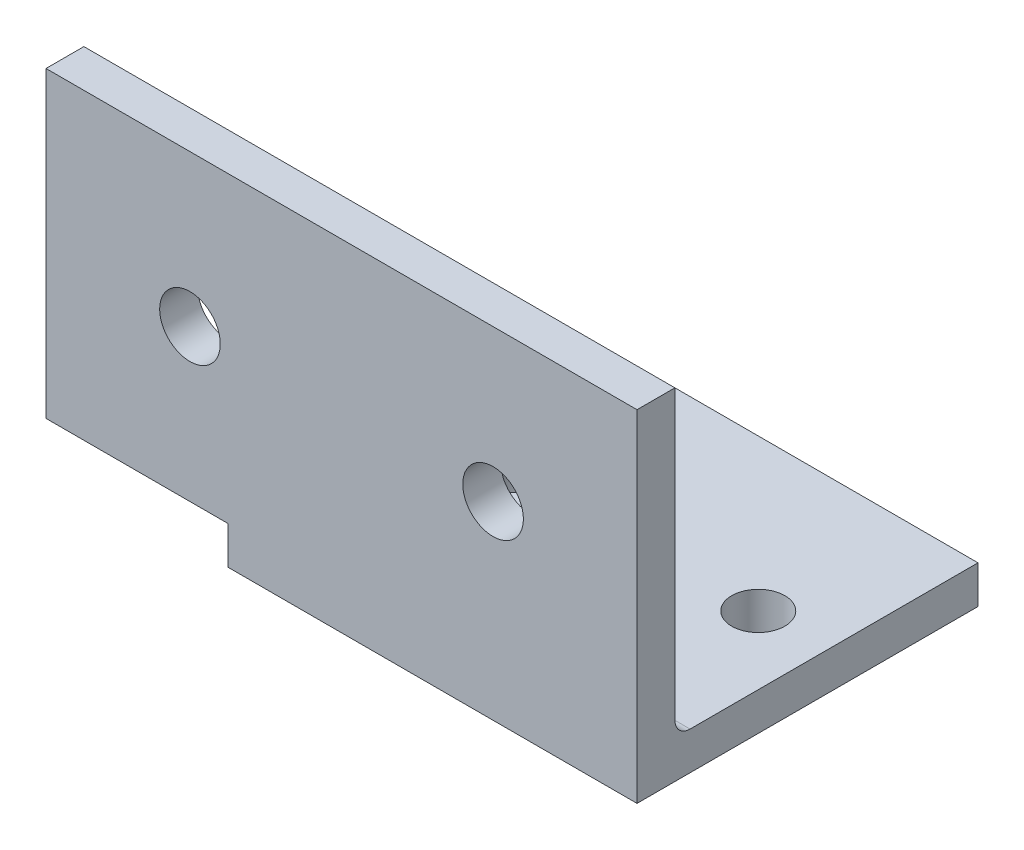
SolidWorks part; units mm, degrees
ref_plane "Front Plane" through (0, 0, 0) normal (0, 0, 1) x (1, 0, 0)
ref_plane "Top Plane" through (0, 0, 0) normal (0, 1, 0) x (1, 0, 0)
ref_plane "Right Plane" through (0, 0, 0) normal (1, 0, 0) x (0, 0, -1)
sketch "Sketch1" plane through (0, 0, 0) normal (0, 1, 0) x (1, 0, 0)
  line L1 (0, 0) -> (49.53, 0)
  line L2 (0, 0) -> (0, 28.575)
  line L3 (0, 28.575) -> (49.53, 28.575)
  line L4 (49.53, 0) -> (49.53, 28.575)
  circle A0 centre (23.495, 15.875) radius 2.2225
  circle A1 centre (43.815, 15.875) radius 2.2225
  dimension "D5" = 4.445
  dimension "D6" = 4.445
  dimension "D1" = 49.53
  dimension "D2" = 28.575
  dimension "D3" = 12.7
  dimension "D4" = 12.7
  dimension "D7" = 20.32
  dimension "D8" = 5.715
extrude "Boss-Extrude1" add sketch "Sketch1" along normal blind 3.175
sketch "Sketch2" plane through (0, 3.175, 0) normal (0, 1, 0) x (1, 0, 0)
  line L0 (49.53, 0) -> (49.53, 28.575) construction
  line L1 (0, 0) -> (49.53, 0)
  line L2 (0, 0) -> (0, 3.175)
  line L3 (0, 3.175) -> (49.53, 3.175)
  line L4 (49.53, 0) -> (49.53, 3.175)
  dimension "D1" = 3.175
extrude "Boss-Extrude2" add sketch "Sketch2" along normal blind 25.4
sketch "Sketch4" plane through (0, 0, -3.175) normal (0, 0, -1) x (-1, 0, 0)
  line L0 (-49.53, 28.575) -> (0, 28.575) construction
  line L1 (-24.765, 28.575) -> (-24.765, 3.175) construction
  line L2 (-49.53, 3.175) -> (0, 3.175) construction
  circle A0 centre (-12.065, 15.875) radius 2.54
  circle A1 centre (-37.465, 15.875) radius 2.54
  dimension "D1" = 5.08
  dimension "D2" = 12.7
  dimension "D3" = 25.4
extrude "Cut-Extrude1" cut sketch "Sketch4" against normal up to surface (3.175 mm away) up to face at (24.765, 14.2875, 0)
sketch "Sketch5" plane through (0, 0, 0) normal (0, -1, 0) x (1, 0, 0)
  line L0 (49.53, -28.575) -> (0, -28.575) construction
  line L1 (0, 0) -> (15.24, 0)
  line L2 (0, 0) -> (0, -28.575)
  line L3 (0, -28.575) -> (15.24, -28.575)
  line L4 (15.24, 0) -> (15.24, -28.575)
  dimension "D1" = 15.24
extrude "Cut-Extrude2" cut sketch "Sketch5" against normal up to surface (3.175 mm away) up to face at (43.815, 3.175, -13.6525)
fillet "Fillet2" radius 1.27 1 edges at (32.385, 3.175, -3.175)
